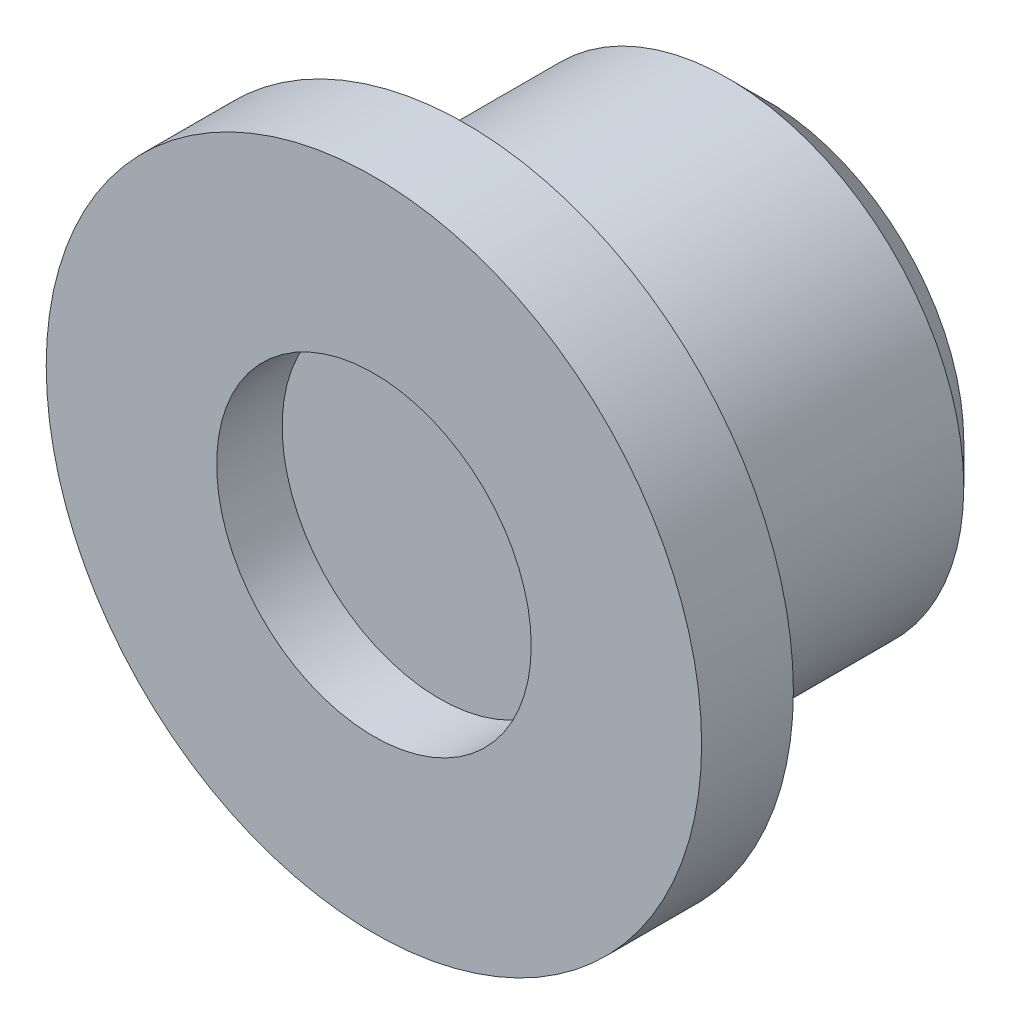
SolidWorks part; units mm, degrees
ref_plane "前视基准面" through (0, 0, 0) normal (0, 0, 1) x (1, 0, 0)
ref_plane "上视基准面" through (0, 0, 0) normal (0, 1, 0) x (1, 0, 0)
ref_plane "右视基准面" through (0, 0, 0) normal (1, 0, 0) x (0, 0, -1)
sketch "草图1" plane through (0, 0, 0) normal (0, 0, 1) x (1, 0, 0)
  circle A0 centre (0, 0) radius 1.8
  dimension "D1" = 3.6
extrude "凸台-拉伸1" add sketch "草图1" along normal blind 3
sketch "草图2" plane through (0, 0, 3) normal (0, 0, 1) x (1, 0, 0)
  circle A0 centre (0, 0) radius 2.5
  circle A1 centre (0, 0) radius 1.8
  circle A2 centre (0, 0) radius 1.8 construction
  dimension "D1" = 0.7
extrude "凸台-拉伸2" add sketch "草图2" against normal blind 0.7
sketch "草图3" plane through (0, 0, 3) normal (0, 0, 1) x (1, 0, 0)
  circle A0 centre (0, 0) radius 1.2
  dimension "D1" = 2.4
extrude "切除-拉伸1" cut sketch "草图3" against normal blind 0.5
chamfer "倒角1" distance 0.3 angle 45 1 edges at (1.8, 0, 0)
